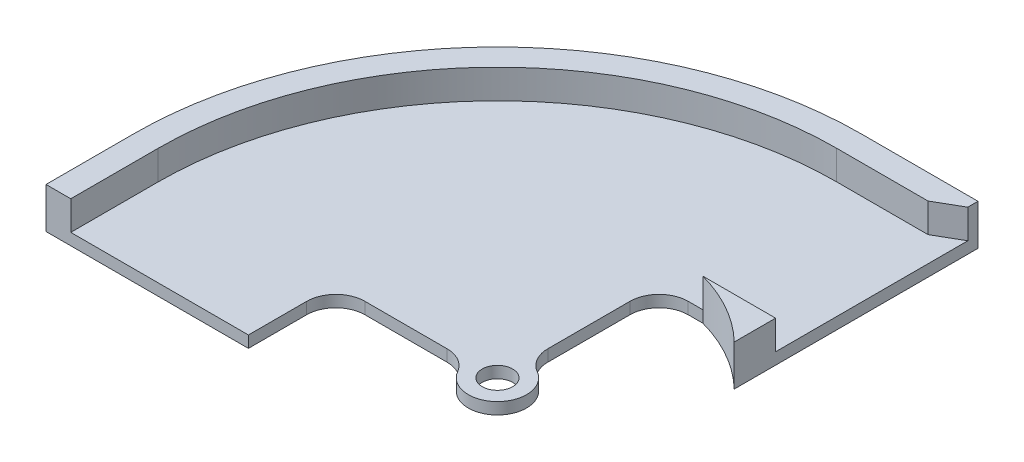
SolidWorks part; units mm, degrees
ref_plane "Front Plane" through (0, 0, 0) normal (0, 0, 1) x (1, 0, 0)
ref_plane "Top Plane" through (0, 0, 0) normal (0, 1, 0) x (1, 0, 0)
ref_plane "Right Plane" through (0, 0, 0) normal (1, 0, 0) x (0, 0, -1)
sketch "Sketch1" plane through (0, 0, 0) normal (0, 1, 0) x (1, 0, 0)
  line L1 (-62.5, 62.5) -> (62.5, 62.5)
  line L2 (-62.5, 62.5) -> (-62.5, -62.5)
  line L3 (-62.5, -62.5) -> (62.5, -62.5)
  line L4 (62.5, 62.5) -> (62.5, -62.5)
  line L5 (-62.5, 62.5) -> (62.5, -62.5) construction
  line L6 (-62.5, -62.5) -> (62.5, 62.5) construction
  circle A0 centre (62.5, -62.5) radius 55.5 construction
  point P0 (0, 0)
  dimension "D2" = 111
  dimension "D3" = 125
  dimension "D1" = 125
extrude "Boss-Extrude1" add sketch "Sketch1" along normal blind 4
sketch "Sketch7" plane through (0, 0, 0) normal (0, 1, 0) x (1, 0, 0)
  line L0 (62.5, 62.5) -> (62.5, -62.5) construction
  line L1 (62.5, -7) -> (102.5, -7)
  line L2 (62.5, -7) -> (62.5, 62.5)
  line L3 (62.5, 62.5) -> (102.5, 62.5)
  line L4 (102.5, -7) -> (102.5, 62.5)
  line L5 (-62.5, 62.5) -> (62.5, 62.5) construction
  circle A0 centre (62.5, -62.5) radius 55.5 construction
  dimension "D1" = 40
extrude "Boss-Extrude4" add sketch "Sketch7" along normal up to surface (4 mm away) up to face at (0, 4, 0)
sketch "Sketch8" plane through (0, 0, 0) normal (0, 1, 0) x (1, 0, 0)
  line L1 (-62.5, -62.5) -> (7, -62.5)
  line L2 (-62.5, -62.5) -> (-62.5, -92.5)
  line L3 (-62.5, -92.5) -> (7, -92.5)
  line L4 (7, -62.5) -> (7, -92.5)
  circle A0 centre (62.5, -62.5) radius 55.5 construction
  dimension "D1" = 30
extrude "Boss-Extrude5" add sketch "Sketch8" along normal up to surface (4 mm away) up to face at (34.1667, 4, 2.3333)
sketch "Sketch2" plane through (0, 4, 0) normal (0, 1, 0) x (1, 0, 0)
  line L0 (-62.5, -92.5) -> (-62.5, 62.5)
  line L1 (-62.5, 62.5) -> (102.5, 62.5)
  line L3 (62.5, -62.5) -> (62.5, -7) construction
  line L5 (7, -62.5) -> (62.5, -62.5) construction
  line L6 (62.5, 54) -> (102.5, 54)
  line L7 (102.5, -7) -> (102.5, 62.5) construction
  line L8 (102.5, 54) -> (102.5, 62.5)
  line L9 (-62.5, -92.5) -> (-54, -92.5)
  line L10 (-62.5, -92.5) -> (7, -92.5) construction
  line L11 (-54, -92.5) -> (-54, -62.5)
  arc A0 (-54, -62.5) -> (62.5, 54) centre (62.5, -62.5) cw
  circle A1 centre (62.5, -62.5) radius 55.5 construction
  dimension "D1" = 111
  dimension "D2" = 61
extrude "Boss-Extrude2" add sketch "Sketch2" along normal blind 10
sketch "Sketch3" plane through (0, 4, 0) normal (0, 1, 0) x (1, 0, 0)
  circle A0 centre (62.5, -62.5) radius 10
  dimension "D1" = 20
extrude "Boss-Extrude3" add sketch "Sketch3" against normal up to surface (4 mm away) up to face at (27.375, 0, 24.875)
sketch "Sketch4" plane through (0, 4, 0) normal (0, 1, 0) x (1, 0, 0)
  circle A0 centre (62.5, -62.5) radius 5.25
  dimension "D1" = 10.5
extrude "Cut-Extrude1" cut sketch "Sketch4" against normal up to surface (4 mm away) up to face at (31.5079, 0, 29.2857)
fillet "Fillet1" radius 125 1 edges at (-62.5, 7, -62.5)
chamfer "Chamfer1" distance 5 angle 60 1 edges at (102.5, 9, -54)
sketch "Sketch9" plane through (0, 0, 0) normal (0, 1, 0) x (1, 0, 0)
  line L0 (102.5, -7) -> (102.5, -21.1932)
  line L1 (102.5, -7) -> (77.5333, -7)
  line L2 (62.5, -7) -> (102.5, -7) construction
  arc A0 (77.5333, -7) -> (102.5, -21.1932) centre (62.5, -62.5) cw
  circle A1 centre (62.5, -62.5) radius 55.5 construction
  dimension "D1" = 2
extrude "Boss-Extrude6" add sketch "Sketch9" along normal up to surface (14 mm away)
fillet "Fillet2" radius 10 4 edges at (62.5, 2, 7) (62.5, 2, 52.5) (52.5, 2, 62.5) (7, 2, 62.5)
